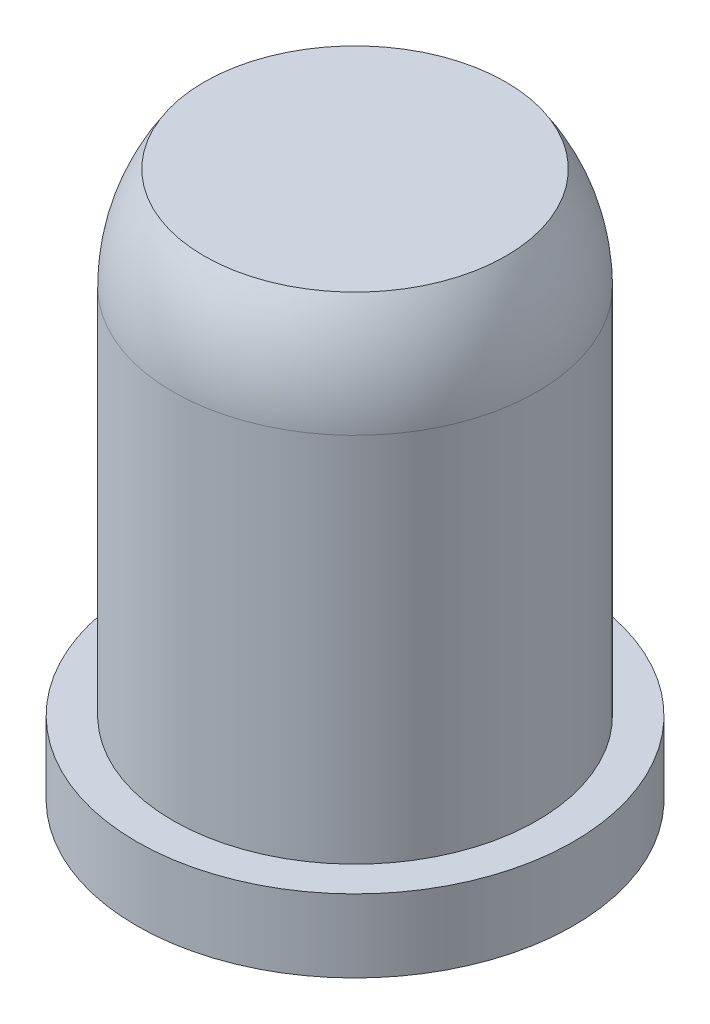
SolidWorks part; units mm, degrees
ref_plane "Спереди" through (0, 0, 0) normal (0, 0, 1) x (1, 0, 0)
ref_plane "Сверху" through (0, 0, 0) normal (0, 1, 0) x (1, 0, 0)
ref_plane "Справа" through (0, 0, 0) normal (1, 0, 0) x (0, 0, -1)
sketch "Эскиз1" plane through (0, 0, 0) normal (0, 1, 0) x (1, 0, 0)
  circle A0 centre (0, 0) radius 3
extrude "Бобышка-Вытянуть1" add sketch "Эскиз1" along normal blind 1
sketch "Эскиз2" plane through (0, 1, 0) normal (0, 1, 0) x (1, 0, 0)
  circle A0 centre (0, 0) radius 2.5
extrude "Бобышка-Вытянуть2" add sketch "Эскиз2" along normal blind 7.6
fillet "Скругление1" radius 2.5 1 edges at (0, 8.6, 2.5)
sketch "Эскиз3" plane through (0, 1, 0) normal (0, 1, 0) x (1, 0, 0)
  circle A0 centre (0, 0) radius 3
ref_plane "Плоскость1" through (0, 8.6, 0) normal (0, 1, 0) x (1, 0, 0)
sketch "Эскиз4" plane through (0, 8.6, 0) normal (0, 1, 0) x (1, 0, 0)
  circle A0 centre (0, 0) radius 2.5567
extrude "Вырез-Вытянуть1" cut sketch "Эскиз4" against normal offset from surface (1.1 mm away) 6.5 up to face at (0, 1, 2.5)
